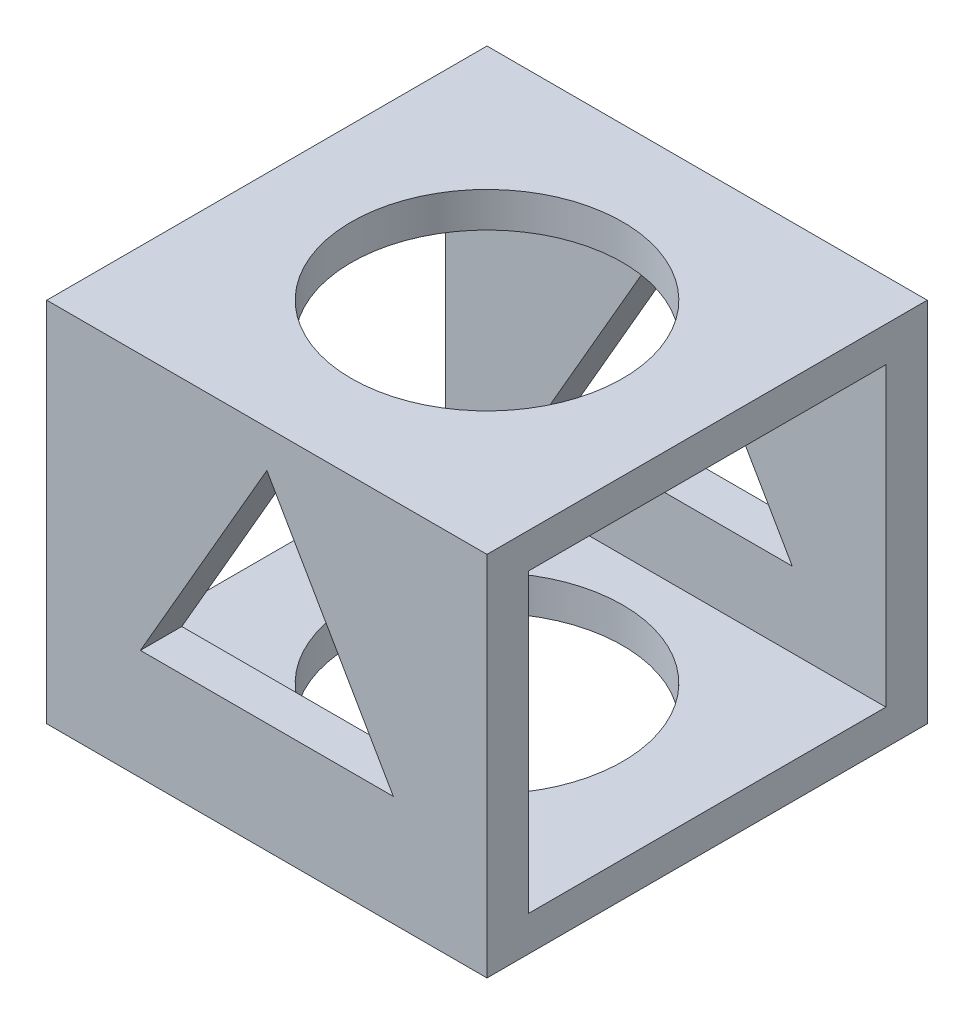
SolidWorks part; units mm, degrees
ref_plane "Front Plane" through (0, 0, 0) normal (0, 0, 1) x (1, 0, 0)
ref_plane "Top Plane" through (0, 0, 0) normal (0, 1, 0) x (1, 0, 0)
ref_plane "Right Plane" through (0, 0, 0) normal (1, 0, 0) x (0, 0, -1)
sketch "Sketch1" plane through (0, 0, 0) normal (0, 0, 1) x (1, 0, 0)
  line L1 (-76.2, -63.5) -> (76.2, -63.5)
  line L2 (-76.2, -63.5) -> (-76.2, 63.5)
  line L3 (-76.2, 63.5) -> (76.2, 63.5)
  line L4 (76.2, -63.5) -> (76.2, 63.5)
  line L5 (-76.2, -63.5) -> (76.2, 63.5) construction
  line L6 (-76.2, 63.5) -> (76.2, -63.5) construction
  point P0 (0, 0)
  dimension "D1" = 152.4
  dimension "D2" = 127
extrude "Boss-Extrude1" add sketch "Sketch1" along normal mid plane 152.4
sketch "Sketch2" plane through (0, 0, 76.2) normal (0, 0, 1) x (1, 0, 0)
  line L1 (0, 50.5506) -> (-43.7781, -25.2753)
  line L2 (-43.7781, -25.2753) -> (43.7781, -25.2753)
  line L3 (43.7781, -25.2753) -> (0, 50.5506)
  circle A0 centre (0, 0) radius 25.2753 construction
extrude "Cut-Extrude1" cut sketch "Sketch2" against normal through all
sketch "Sketch3" plane through (76.2, 0, 0) normal (1, 0, 0) x (0, 0, -1)
  line L1 (-61.8845, -51.332) -> (61.8845, -51.332)
  line L2 (-61.8845, -51.332) -> (-61.8845, 51.332)
  line L3 (-61.8845, 51.332) -> (61.8845, 51.332)
  line L4 (61.8845, -51.332) -> (61.8845, 51.332)
  line L5 (-61.8845, -51.332) -> (61.8845, 51.332) construction
  line L6 (-61.8845, 51.332) -> (61.8845, -51.332) construction
  point P0 (0, 0)
extrude "Cut-Extrude2" cut sketch "Sketch3" against normal through all
sketch "Sketch4" plane through (0, 63.5, 0) normal (0, 1, 0) x (1, 0, 0)
  circle A0 centre (0, 0) radius 46.9609
extrude "Cut-Extrude3" cut sketch "Sketch4" against normal through all
